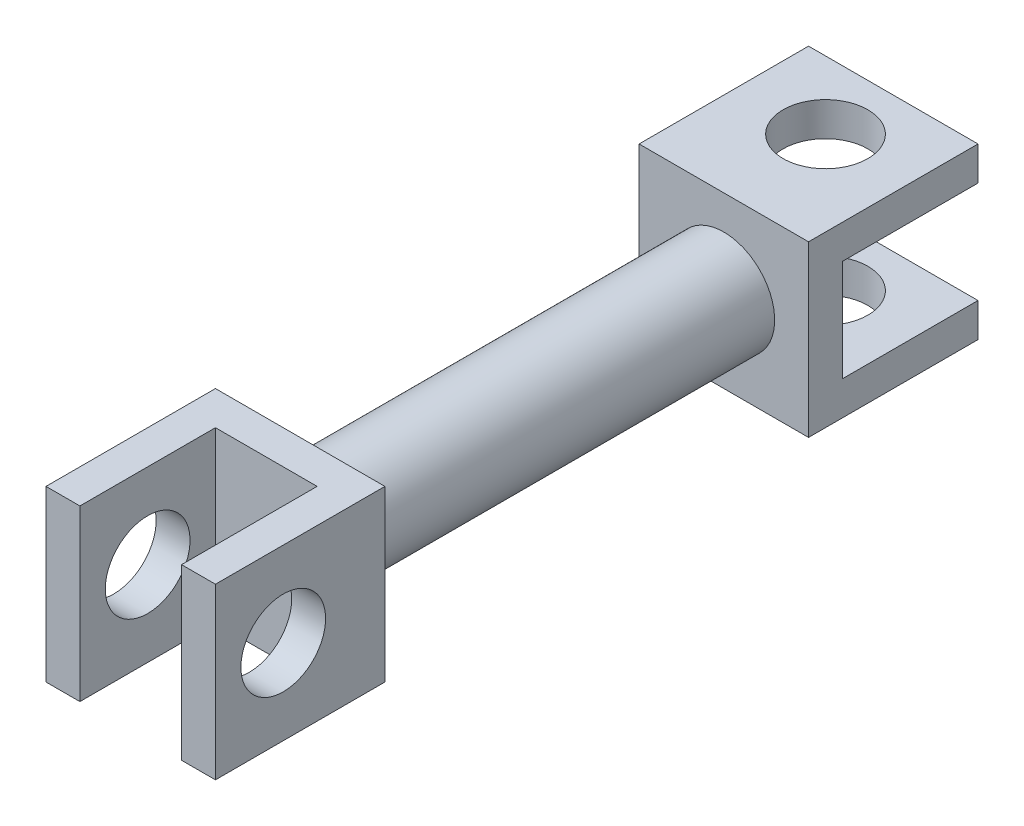
SolidWorks part; units mm, degrees
ref_plane "Front Plane" through (0, 0, 0) normal (0, 0, 1) x (1, 0, 0)
ref_plane "Top Plane" through (0, 0, 0) normal (0, 1, 0) x (1, 0, 0)
ref_plane "Right Plane" through (0, 0, 0) normal (1, 0, 0) x (0, 0, -1)
sketch "Sketch1" plane through (0, 0, 0) normal (0, 0, 1) x (1, 0, 0)
  line L1 (-5, 5) -> (5, 5)
  line L2 (-5, 5) -> (-5, -5)
  line L3 (-5, -5) -> (5, -5)
  line L4 (5, 5) -> (5, -5)
  line L5 (-5, 5) -> (5, -5) construction
  line L6 (-5, -5) -> (5, 5) construction
  point P0 (0, 0)
  dimension "D1" = 10
  dimension "D2" = 10
extrude "Boss-Extrude1" add sketch "Sketch1" along normal blind 2
sketch "Sketch2" plane through (0, 0, 2) normal (0, 0, 1) x (1, 0, 0)
  line L0 (5, 5) -> (-5, 5) construction
  line L1 (-5, -5) -> (-3, -5)
  line L2 (-5, -5) -> (-5, 5)
  line L3 (-5, 5) -> (-3, 5)
  line L4 (-3, -5) -> (-3, 5)
  line L6 (3, 5) -> (5, 5)
  line L7 (3, 5) -> (3, -5)
  line L8 (3, -5) -> (5, -5)
  line L9 (5, 5) -> (5, -5)
  dimension "D1" = 2
  dimension "D2" = 2
extrude "Boss-Extrude2" add sketch "Sketch2" along normal blind 8
sketch "Sketch3" plane through (-5, 0, 0) normal (-1, 0, 0) x (0, 0, 1)
  line L0 (0, 5) -> (0, -5) construction
  line L1 (10, -5) -> (0, -5) construction
  circle A0 centre (6, 0) radius 2.5
  dimension "D1" = 6
  dimension "D2" = 5
extrude "Cut-Extrude1" cut sketch "Sketch3" against normal through all
sketch "Sketch4" plane through (0, 0, 0) normal (0, 0, -1) x (-1, 0, 0)
  circle A0 centre (0, 0) radius 3
extrude "Boss-Extrude3" add sketch "Sketch4" along normal blind 25
ref_plane "Plane1" through (0, 0, -25) normal (0, 0, -1) x (-1, 0, 0)
sketch "Sketch5" plane through (0, 0, -25) normal (0, 0, -1) x (-1, 0, 0)
  line L1 (-5, -5) -> (5, -5)
  line L2 (-5, -5) -> (-5, 5)
  line L3 (-5, 5) -> (5, 5)
  line L4 (5, -5) -> (5, 5)
extrude "Boss-Extrude4" add sketch "Sketch5" along normal blind 2
sketch "Sketch6" plane through (0, 0, -27) normal (0, 0, -1) x (-1, 0, 0)
  line L0 (-5, 5) -> (-5, -5) construction
  line L1 (5, -5) -> (-5, -5)
  line L2 (5, -5) -> (5, -3)
  line L3 (5, -3) -> (-5, -3)
  line L4 (-5, -5) -> (-5, -3)
  line L6 (-5, 3) -> (5, 3)
  line L7 (-5, 3) -> (-5, 5)
  line L8 (-5, 5) -> (5, 5)
  line L9 (5, 3) -> (5, 5)
  dimension "D1" = 2
  dimension "D2" = 2
extrude "Boss-Extrude5" add sketch "Sketch6" along normal blind 8
sketch "Sketch7" plane through (0, -5, 0) normal (0, -1, 0) x (1, 0, 0)
  line L0 (5, -25) -> (-5, -25) construction
  line L1 (-5, -35) -> (-5, -25) construction
  circle A0 centre (0, -31) radius 2.5
  dimension "D1" = 6
  dimension "D2" = 5
extrude "Cut-Extrude2" cut sketch "Sketch7" against normal through all
